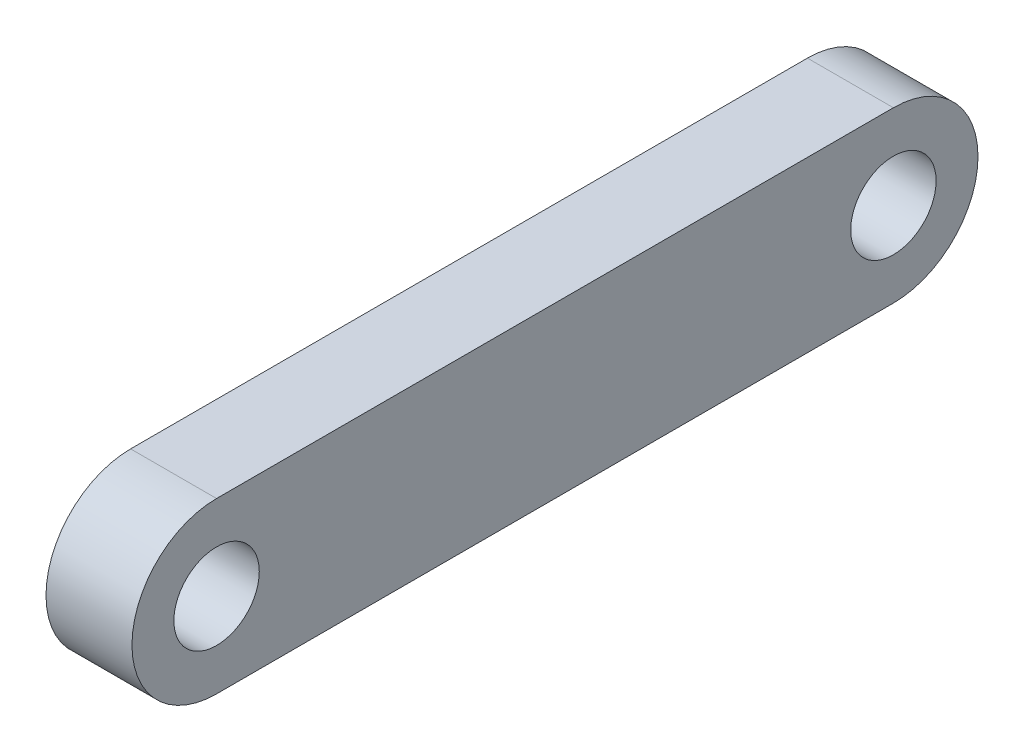
SolidWorks part; units mm, degrees
material "6061-T6 (SS)"
ref_plane "Front Plane" through (0, 0, 0) normal (0, 0, 1) x (1, 0, 0)
ref_plane "Top Plane" through (0, 0, 0) normal (0, 1, 0) x (1, 0, 0)
ref_plane "Right Plane" through (0, 0, 0) normal (1, 0, 0) x (0, 0, -1)
sketch "Sketch1" plane through (0, 0, 0) normal (1, 0, 0) x (0, 0, -1)
  line L0 (0, 0) -> (32, 0) construction
  line L1 (0, 4) -> (32, 4)
  line L2 (0, -4) -> (32, -4)
  arc A0 (0, 4) -> (0, -4) centre (0, 0) ccw
  arc A1 (32, -4) -> (32, 4) centre (32, 0) ccw
  circle A2 centre (0, 0) radius 2.0193
  circle A3 centre (32, 0) radius 2.0193
  point P3 (16, 0)
  dimension "D1" = 4
  dimension "D3" = 4.0386
  dimension "D2" = 32
extrude "Boss-Extrude1" add sketch "Sketch1" along normal blind 4.064
